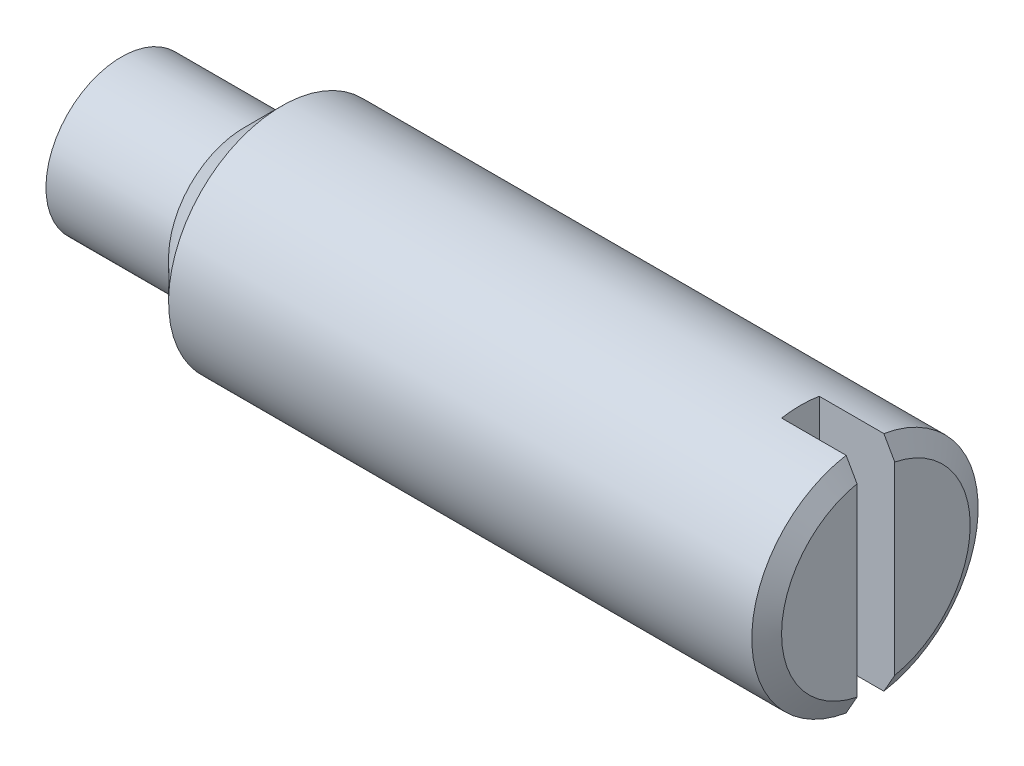
SolidWorks part; units mm, degrees
material "AISI 1020"
ref_plane "Front Plane" through (0, 0, 0) normal (0, 0, 1) x (1, 0, 0)
ref_plane "Top Plane" through (0, 0, 0) normal (0, 1, 0) x (1, 0, 0)
ref_plane "Right Plane" through (0, 0, 0) normal (1, 0, 0) x (0, 0, -1)
sketch "Sketch1" plane through (0, 0, 0) normal (0, 0, 1) x (1, 0, 0)
  line L0 (0, 0) -> (0, 3)
  line L1 (0, 3) -> (-15.75, 3)
  line L2 (-15.75, 3) -> (-16.75, 2)
  line L3 (-16.75, 2) -> (-20, 2)
  line L4 (-20, 2) -> (-20, 0)
  line L5 (-20, 0) -> (0, 0) construction
  line L6 (0, 0) -> (-20, 0)
  dimension "Diam" = 6
  dimension "S_diam" = 4
  dimension "D3" = 45
  dimension "S_ilgis" = 3.25
  dimension "Ilgis" = 20
revolve "Revolve1" add sketch "Sketch1" angle 360 about L5
cosmetic thread "Cosmetic Thread1" parameters "Sr_diam"=5
chamfer "Chamfer1" distance 0.5 angle 30 1 edges at (0, -3, 0)
sketch "Sketch2" plane through (0, 0, 0) normal (1, 0, 0) x (0, 0, -1)
  line L0 (-0.5, -3) -> (0.5, 3) construction
  line L1 (-0.5, 3) -> (0.5, 3)
  line L2 (-0.5, 3) -> (-0.5, -3)
  line L3 (-0.5, -3) -> (0.5, -3)
  line L4 (0.5, 3) -> (0.5, -3)
  circle A1 centre (0, 0) radius 3 construction
  dimension "Y_plotis" = 1
extrude "Cut-Extrude2" cut sketch "Sketch2" against normal blind 2
